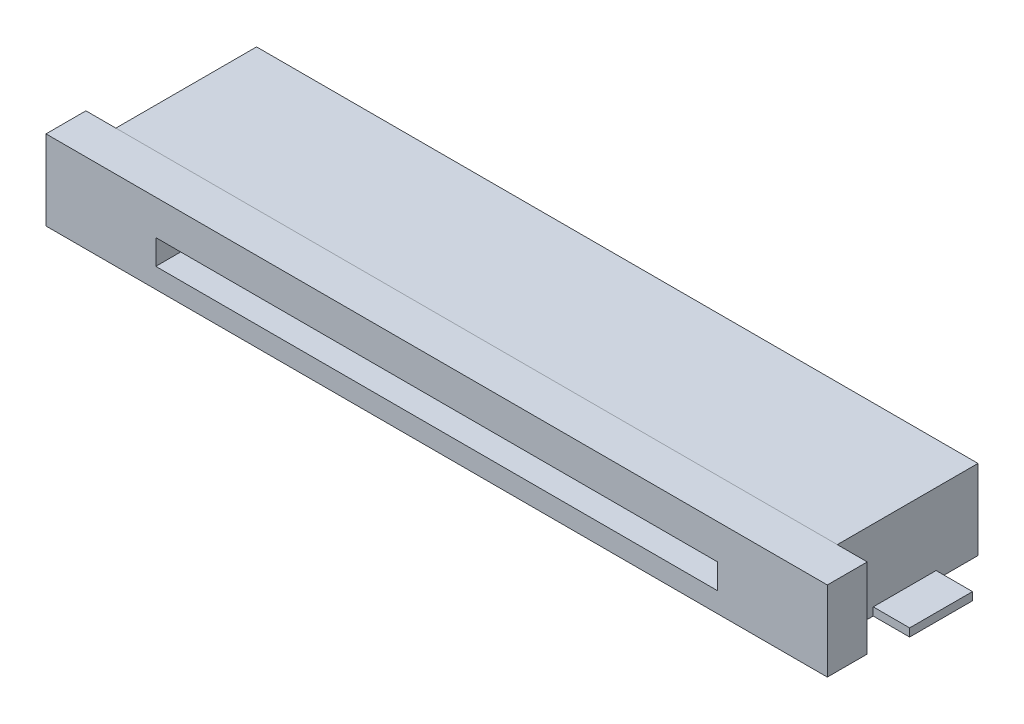
SolidWorks part; units mm, degrees
ref_plane "Front" through (0, 0, 0) normal (0, 0, 1) x (1, 0, 0)
ref_plane "Top" through (0, 0, 0) normal (0, 1, 0) x (1, 0, 0)
ref_plane "Right" through (0, 0, 0) normal (1, 0, 0) x (0, 0, -1)
sketch "Sketch1" plane through (0, 0, 0) normal (0, 0, 1) x (1, 0, 0)
  line L1 (-9.9441, 0) -> (9.9441, 0)
  line L2 (-9.9441, 0) -> (-9.9441, 2.032)
  line L3 (-9.9441, 2.032) -> (9.9441, 2.032)
  line L4 (9.9441, 0) -> (9.9441, 2.032)
  dimension "D1" = 2.032
  dimension "D2" = 19.8882
extrude "Extrude1" add sketch "Sketch1" along normal blind 1.016
sketch "Sketch2" plane through (0, 0, 0) normal (0, 0, -1) x (-1, 0, 0)
  line L0 (-9.9441, 2.032) -> (9.9441, 2.032) construction
  line L1 (-9.1821, 2.032) -> (9.1821, 2.032)
  line L2 (-9.1821, 2.032) -> (-9.1821, 0)
  line L3 (-9.1821, 0) -> (9.1821, 0)
  line L4 (9.1821, 2.032) -> (9.1821, 0)
  line L5 (9.9441, 0) -> (-9.9441, 0) construction
  line L6 (-9.9441, 0) -> (-9.9441, 2.032) construction
  line L7 (9.9441, 2.032) -> (9.9441, 0) construction
  dimension "D1" = 0.762
  dimension "D2" = 0.762
extrude "Extrude2" add sketch "Sketch2" along normal blind 3.5814
sketch "Sketch3" plane through (0, 2.032, 0) normal (0, 1, 0) x (1, 0, 0)
  line L0 (-9.1821, 0) -> (9.1821, 0)
split line "Split Line1"
sketch "Sketch4" plane through (0, 0, 0) normal (0, -1, 0) x (1, 0, 0)
  line L0 (-9.1821, 0) -> (-7.1501, 0)
  line L1 (-7.1501, 0) -> (-7.1501, 1.016)
  line L2 (-9.9441, 1.016) -> (9.9441, 1.016) construction
  line L5 (-9.9441, 1.016) -> (-9.9441, 0) construction
  dimension "D1" = 2.794
split line "Split Line3"
sketch "Sketch5" plane through (0, 0, 0) normal (0, -1, 0) x (1, 0, 0)
  line L0 (9.1821, 0) -> (7.1501, 0)
  line L1 (7.1501, 0) -> (7.1501, 1.016)
  line L2 (-7.1501, 1.016) -> (9.9441, 1.016) construction
  line L3 (9.9441, 1.016) -> (9.9441, 0) construction
  dimension "D1" = 2.794
split line "Split Line4"
sketch "Sketch6" plane through (0, 0, 1.016) normal (0, 0, 1) x (1, 0, 0)
  line L0 (9.9441, 2.032) -> (-9.9441, 2.032) construction
  line L2 (-7.1501, 0.508) -> (-7.1501, 1.143)
  line L3 (-7.1501, 1.143) -> (7.1501, 1.143)
  line L4 (7.1501, 0.508) -> (7.1501, 1.143)
  line L5 (-7.1501, 0.508) -> (7.1501, 0.508)
  dimension "D1" = 0.889
  dimension "D2" = 0.635
extrude "Cut-Extrude1" cut sketch "Sketch6" against normal blind 3.302
sketch "Sketch7" plane through (0, 0, 0) normal (0, -1, 0) x (1, 0, 0)
  line L0 (9.1821, -3.5814) -> (-9.1821, -3.5814) construction
  line L1 (-0.381, -3.5306) -> (-0.127, -3.5306)
  line L2 (-0.381, -3.5306) -> (-0.381, -4.2926)
  line L3 (-0.381, -4.2926) -> (-0.127, -4.2926)
  line L4 (-0.127, -3.5306) -> (-0.127, -4.2926)
  dimension "D1" = 0.254
  dimension "D2" = 0.7112
  dimension "D3" = 0.762
  dimension "D4" = 0.127
extrude "Extrude3" add sketch "Sketch7" against normal blind 0.2032
pattern_linear "LPattern1" count 15 spacing 0.508 along (1, 0, 0) of "Extrude3"
pattern_linear "LPattern2" count 14 spacing 0.508 along (-1, 0, 0) of "Extrude3"
sketch "Sketch8" plane through (6.985, 0, 0) normal (1, 0, 0) x (0, 0, -1)
  line L0 (4.2926, 0) -> (3.5814, 0) construction
  line L1 (3.5814, 0.2032) -> (3.7846, 0.2032)
  line L2 (3.5814, 0.2032) -> (3.5814, 0.762)
  line L3 (3.5814, 0.762) -> (3.7846, 0.762)
  line L4 (3.7846, 0.2032) -> (3.7846, 0.762)
  dimension "D1" = 0.2032
  dimension "D2" = 0.762
extrude "Extrude4" add sketch "Sketch8" against normal blind 0.254
pattern_linear "LPattern3" count 28 spacing 0.508 along (-1, 0, 0) of "Extrude4"
chamfer "Chamfer1" distance 0.127 angle 45 28 edges at (6.858, 0.762, -3.7846) (-6.858, 0.762, -3.7846) (-6.35, 0.762, -3.7846) (-5.842, 0.762, -3.7846) (-5.334, 0.762, -3.7846) (-4.826, 0.762, -3.7846) (-4.318, 0.762, -3.7846) (-3.81, 0.762, -3.7846) (-3.302, 0.762, -3.7846) (-2.794, 0.762, -3.7846) (-2.286, 0.762, -3.7846) (-1.778, 0.762, -3.7846) (-1.27, 0.762, -3.7846) (-0.762, 0.762, -3.7846) (-0.254, 0.762, -3.7846) (0.254, 0.762, -3.7846) (0.762, 0.762, -3.7846) (1.27, 0.762, -3.7846) (1.778, 0.762, -3.7846) (2.286, 0.762, -3.7846) (2.794, 0.762, -3.7846) (3.302, 0.762, -3.7846) (3.81, 0.762, -3.7846) (4.318, 0.762, -3.7846) (4.826, 0.762, -3.7846) (5.334, 0.762, -3.7846) (5.842, 0.762, -3.7846) (6.35, 0.762, -3.7846)
sketch "Sketch9" plane through (0, 0, 0) normal (0, -1, 0) x (1, 0, 0)
  line L0 (-6.985, -3.5814) -> (-6.985, -4.2926) construction
  line L1 (-10.1092, -0.9144) -> (-8.001, -0.9144)
  line L2 (-10.1092, -0.9144) -> (-10.1092, -2.5146)
  line L3 (-10.1092, -2.5146) -> (-8.001, -2.5146)
  line L4 (-8.001, -0.9144) -> (-8.001, -2.5146)
  line L5 (8.001, -0.9144) -> (10.1092, -0.9144)
  line L6 (8.001, -0.9144) -> (8.001, -2.5146)
  line L7 (8.001, -2.5146) -> (10.1092, -2.5146)
  line L8 (10.1092, -0.9144) -> (10.1092, -2.5146)
  line L9 (6.985, -4.2926) -> (6.985, -3.5814) construction
  dimension "D1" = 1.778
  dimension "D2" = 2.1082
  dimension "D3" = 1.6002
  dimension "D4" = 1.016
  dimension "D5" = 1.016
  dimension "D6" = 2.1082
extrude "Extrude5" add sketch "Sketch9" against normal blind 0.2032
sketch "Sketch10" plane through (0, 0, 0) normal (0, -1, 0) x (1, 0, 0)
  line L0 (9.1821, -0.9144) -> (8.001, -0.9144)
  line L1 (8.001, -0.9144) -> (8.001, -2.5146)
  line L2 (8.001, -2.5146) -> (9.1821, -2.5146)
  line L3 (10.1092, -2.5146) -> (10.1092, -0.9144) construction
  dimension "D1" = 2.1082
split line "Split Line5"
sketch "Sketch11" plane through (0, 0, 0) normal (0, -1, 0) x (1, 0, 0)
  line L0 (-9.1821, -0.9144) -> (-8.001, -0.9144)
  line L1 (-10.1092, -0.9144) -> (-10.1092, -2.5146) construction
  line L2 (-8.001, -2.5146) -> (-8.001, -0.9144)
  line L3 (-8.001, -2.5146) -> (-9.1821, -2.5146)
  dimension "D1" = 2.1082
split line "Split Line6"
sketch "Sketch12" plane through (0, 0, 0) normal (0, -1, 0) x (1, 0, 0)
  line L0 (-6.985, -3.5814) -> (6.985, -3.5814)
split line "Split Line7"
